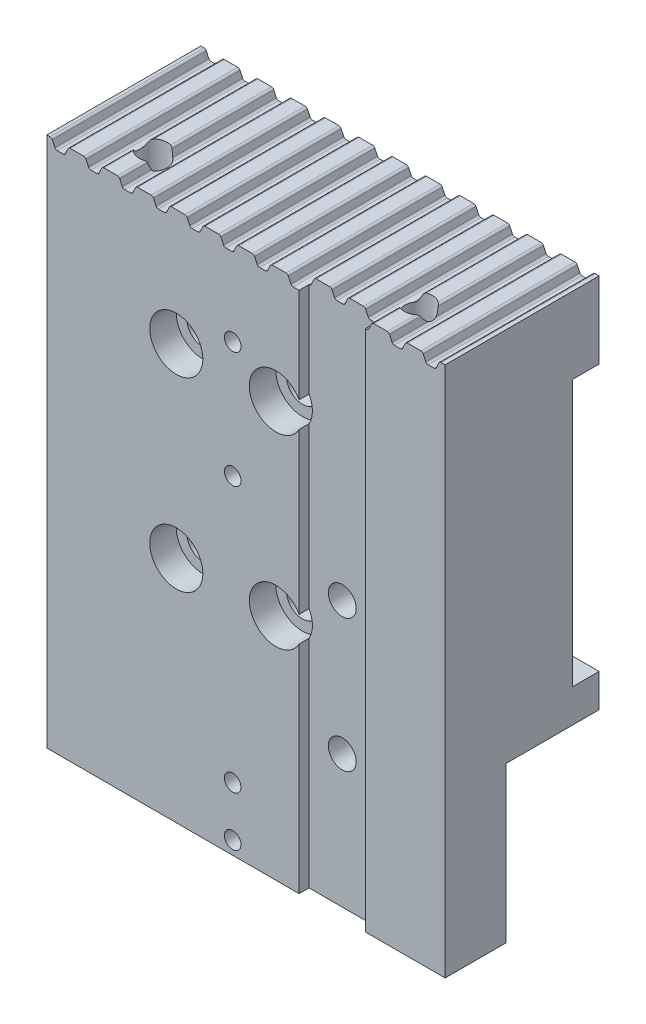
SolidWorks part; units mm, degrees
material "SKD11淬火HRC56-60"
ref_plane "前基準面" through (0, 0, 0) normal (0, 0, 1) x (1, 0, 0)
ref_plane "上基準面" through (0, 0, 0) normal (0, 1, 0) x (1, 0, 0)
ref_plane "右基準面" through (0, 0, 0) normal (1, 0, 0) x (0, 0, -1)
sketch "草图1" plane through (0, 0, 0) normal (0, 0, 1) x (1, 0, 0)
  line L1 (0, 0) -> (60, 0)
  line L2 (0, 0) -> (0, 80)
  line L3 (0, 80) -> (60, 80)
  line L4 (60, 0) -> (60, 80)
  dimension "D1" = 80
  dimension "D2" = 60
extrude "凸台-拉伸1" add sketch "草图1" against normal blind 23.2
sketch "草图2" plane through (0, 0, 0) normal (-1, 0, 0) x (0, 0, 1)
  line L0 (-23.2, 80) -> (-23.2, 0) construction
  line L1 (-23.2, 68.5) -> (-19.2, 68.5)
  line L2 (-23.2, 68.5) -> (-23.2, 28.4)
  line L3 (-23.2, 28.4) -> (-19.2, 28.4)
  line L4 (-19.2, 68.5) -> (-19.2, 28.4)
  line L5 (-23.2, 80) -> (0, 80) construction
  dimension "D1" = 40.1
  dimension "D2" = 4
  dimension "D3" = 11.5
extrude "切除-拉伸1" cut sketch "草图2" against normal through all
sketch "草图3" plane through (0, 0, 0) normal (0, 0, 1) x (1, 0, 0)
  line L0 (0.715, 80) -> (1.3072, 78.73)
  line L1 (60, 80) -> (0, 80) construction
  line L2 (1.3072, 78.73) -> (2.6928, 78.73)
  line L3 (2, 78.73) -> (2, 80) construction
  line L4 (3.285, 80) -> (2.6928, 78.73)
  line L5 (0.715, 80) -> (3.285, 80)
  line L6 (0, 80) -> (0, 0) construction
  dimension "D1" = 50
  dimension "D2" = 1.27
  dimension "D3" = 2.57
  dimension "D4" = 2
extrude "切除-拉伸2" cut sketch "草图3" against normal through all
fillet "圆角1" radius 0.38 4 edges at (3.285, 80, -11.6) (2.6928, 78.73, -11.6) (1.3072, 78.73, -11.6) (0.715, 80, -11.6)
pattern_linear "阵列(线性)1" count 12 spacing 5.08 along (1, 0, 0) of "切除-拉伸2", "圆角1"
sketch "草图5" plane through (0, 0, 0) normal (-1, 0, 0) x (0, 0, 1)
  line L0 (-23.2, 0) -> (0, 0) construction
  line L1 (-23.2, 0) -> (-9.2, 0)
  line L2 (-23.2, 0) -> (-23.2, 23.4)
  line L3 (-23.2, 23.4) -> (-9.2, 23.4)
  line L4 (-9.2, 0) -> (-9.2, 23.4)
  line L5 (-23.2, 28.4) -> (-19.2, 28.4) construction
  dimension "D1" = 5
  dimension "D2" = 14
extrude "切除-拉伸4" cut sketch "草图5" against normal through all
sketch "草图6" plane through (0, 0, 0) normal (0, 0, 1) x (1, 0, 0)
  line L0 (0, 0) -> (60, 0) construction
  line L1 (38, 0) -> (48, 0)
  line L2 (38, 0) -> (38, 85)
  line L3 (38, 85) -> (48, 85)
  line L4 (48, 0) -> (48, 85)
  line L5 (0, 80) -> (0, 0) construction
  dimension "D1" = 10
  dimension "D2" = 38
  dimension "D3" = 85
extrude "切除-拉伸5" cut sketch "草图6" against normal blind 1.5
hole_wizard "M5 螺纹孔1" positions "草图8" profile "草图7" tap size "M5" standard "ISO"
sketch "草图8" plane through (0, 80, 0) normal (0, 1, 0) x (-1, 0, 0)
  point P0 (-10, -6)
  point P4 (-50, -6)
sketch "草图7" plane through (10, 80, -6) normal (1, 0, 0) x (0, 0, 1)
  line L0 (0, 0) -> (0, 13.6618)
  line L1 (0, 13.6618) -> (2.1, 12.4)
  line L2 (2.1, 12.4) -> (2.1, 0)
  line L5 (2.1, 0) -> (0, 0)
  line L10 (0, 13.6618) -> (-2.1, 12.4) construction
  line L11 (0, -6.35) -> (0, 107.95) construction
  dimension "螺纹孔钻头直径" = 4.2
  dimension "螺纹孔钻头深度" = 12.4
  dimension "导头角度" = 118
cosmetic thread "孔螺蚊线1" parameters "D1"=10, "D2"=5
cosmetic thread "孔螺蚊线2" parameters "D1"=10, "D2"=5
hole_wizard "M5 螺纹孔2" positions "草图10" profile "草图9" tap size "M5" standard "ISO"
sketch "草图10" plane through (0, 0, -1.5) normal (0, 0, 1) x (1, 0, 0)
  line L0 (38, 0) -> (48, 0) construction
  line L1 (48, 0) -> (48, 78.73) construction
  point P0 (43, 40)
  point P1 (43, 20)
  dimension "D1" = 20
  dimension "D2" = 20
  dimension "D3" = 5
sketch "草图9" plane through (43, 40, -1.5) normal (1, 0, 0) x (0, -1, 0)
  line L0 (0, 0) -> (0, 13.6618)
  line L1 (0, 13.6618) -> (2.1, 12.4)
  line L2 (2.1, 12.4) -> (2.1, 0)
  line L5 (2.1, 0) -> (0, 0)
  line L10 (0, 13.6618) -> (-2.1, 12.4) construction
  line L11 (0, -6.35) -> (0, 107.95) construction
  dimension "螺纹孔钻头直径" = 4.2
  dimension "螺纹孔钻头深度" = 12.4
  dimension "导头角度" = 118
cosmetic thread "孔螺蚊线3" parameters "D1"=7.7, "D2"=5
cosmetic thread "孔螺蚊线4" parameters "D1"=10, "D2"=5
hole_wizard "M3 螺纹孔1" positions "草图12" profile "草图11" tap size "M3" standard "ISO" end condition through all
sketch "草图12" plane through (0, 0, 0) normal (0, 0, 1) x (1, 0, 0)
  point P0 (28, 9.5)
  point P4 (28, 67)
cosmetic thread "孔螺蚊线5" parameters "D2"=3
cosmetic thread "孔螺蚊线6" parameters "D2"=3
sketch "草图11" plane through (28, 9.5, 0) normal (1, 0, 0) x (0, -1, 0)
  line L0 (0, 0) -> (0, 23.2)
  line L1 (0, 23.2) -> (1.25, 23.2)
  line L2 (1.25, 23.2) -> (1.25, 0)
  line L5 (1.25, 0) -> (0, 0)
  line L11 (0, -6.35) -> (0, 107.95) construction
  dimension "通孔螺纹孔钻头直径" = 2.5
  dimension "通孔螺纹孔钻头深度" = 23.2
hole_wizard "M4 六角凹头螺钉的柱形沉头孔1" positions "草图14" profile "草图13" counterbore size "M4" standard "ISO" end condition through all
sketch "草图14" plane through (0, 0, 0) normal (0, 0, 1) x (1, 0, 0)
  point P1 (19.5, 62.5)
  point P4 (34.5, 62.5)
  point P7 (34.5, 34.5)
  point P10 (19.5, 34.5)
sketch "草图13" plane through (19.5, 62.5, 0) normal (1, 0, 0) x (0, -1, 0)
  line L0 (0, 0) -> (0, 23.2)
  line L1 (0, 23.2) -> (2.4, 23.2)
  line L3 (2.4, 23.2) -> (2.4, 4)
  line L4 (2.4, 4) -> (4, 4)
  line L5 (4, 4) -> (4, 0)
  line L7 (4, 0) -> (0, 0)
  line L11 (0, -6.35) -> (0, 107.95) construction
  dimension "通孔孔直径" = 4.8
  dimension "通孔孔深度" = 23.2
  dimension "柱形沉头孔直径" = 8
  dimension "柱形沉头孔深度" = 4
hole_wizard "M3 螺纹孔2" positions "草图16" profile "草图15" tap size "M3" standard "ISO" end condition through all
sketch "草图16" plane through (0, 0, 0) normal (0, 0, 1) x (1, 0, 0)
  line L0 (28, 67) -> (28, -14.6502) construction
  line L1 (0, 0) -> (38, 0) construction
  point P0 (28, 2)
  point P1 (28, 49.5)
  dimension "D1" = 2
  dimension "D2" = 47.5
cosmetic thread "孔螺蚊线7" parameters "D2"=3
cosmetic thread "孔螺蚊线8" parameters "D2"=3
sketch "草图15" plane through (28, 2, 0) normal (1, 0, 0) x (0, -1, 0)
  line L0 (0, 0) -> (0, 23.2)
  line L1 (0, 23.2) -> (1.25, 23.2)
  line L2 (1.25, 23.2) -> (1.25, 0)
  line L5 (1.25, 0) -> (0, 0)
  line L11 (0, -6.35) -> (0, 107.95) construction
  dimension "通孔螺纹孔钻头直径" = 2.5
  dimension "通孔螺纹孔钻头深度" = 23.2
hole_wizard "M5 螺纹孔3" positions "草图18" profile "草图17" tap size "M5" standard "ISO"
sketch "草图18" plane through (0, 0, 0) normal (-1, 0, 0) x (0, 0, 1)
  line L0 (-9.2, 0) -> (0, 0) construction
  line L1 (0, 80) -> (0, 0) construction
  point P0 (-6, 45)
  dimension "D1" = 45
  dimension "D2" = 6
sketch "草图17" plane through (0, 45, -6) normal (0, 1, 0) x (0, 0, 1)
  line L0 (0, 0) -> (0, 13.6618)
  line L1 (0, 13.6618) -> (2.1, 12.4)
  line L2 (2.1, 12.4) -> (2.1, 0)
  line L5 (2.1, 0) -> (0, 0)
  line L10 (0, 13.6618) -> (-2.1, 12.4) construction
  line L11 (0, -6.35) -> (0, 107.95) construction
  dimension "螺纹孔钻头直径" = 4.2
  dimension "螺纹孔钻头深度" = 12.4
  dimension "导头角度" = 118
cosmetic thread "孔螺蚊线9" parameters "D1"=10, "D2"=5
